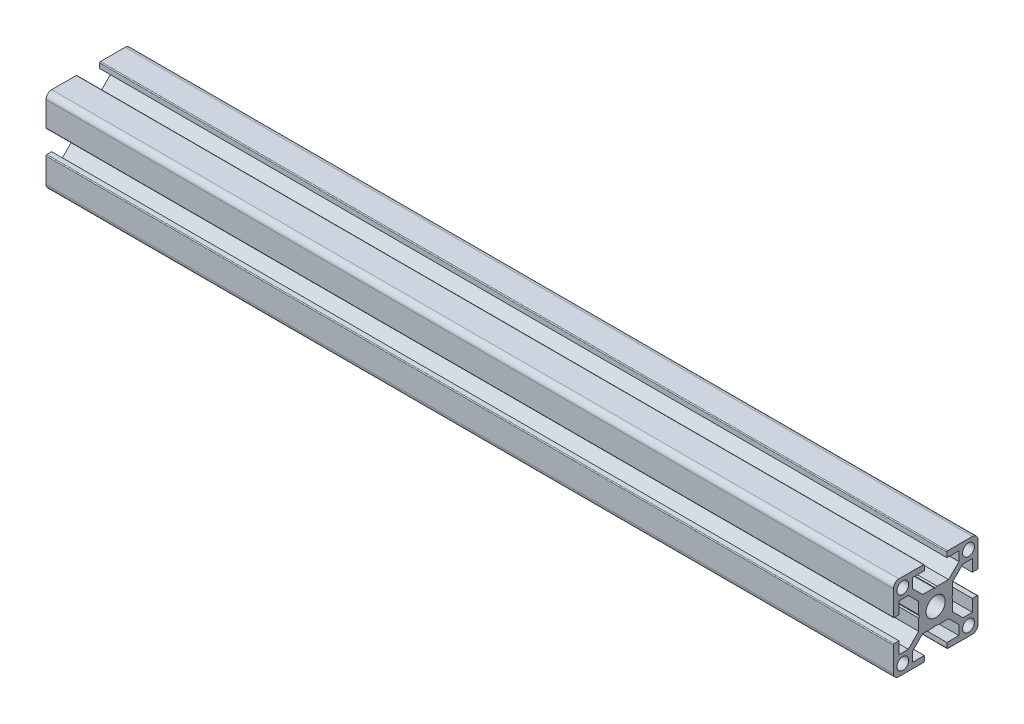
SolidWorks part; units mm, degrees
ref_plane "Front Plane" through (0, 0, 0) normal (0, 0, 1) x (1, 0, 0)
ref_plane "Top Plane" through (0, 0, 0) normal (0, 1, 0) x (1, 0, 0)
ref_plane "Right Plane" through (0, 0, 0) normal (1, 0, 0) x (0, 0, -1)
sketch "Sketch1" plane through (0, 0, 0) normal (0, 0, 1) x (1, 0, 0)
  line L0 (0, 0) -> (300, 0)
  dimension "D1" = 300
other "30xs6 30X30S6(1)"
ref_plane "Plane1" through (0, 0, 0) normal (1, 0, 0) x (0, 1, 0)
sketch "草图1" plane through (0, 0, 0) normal (1, 0, 0) x (0, 1, 0)
  line L0 (-14.7, 4) -> (-13, 4)
  line L1 (-13, 4) -> (-13, 8.25)
  line L2 (-13, 8.25) -> (-9.6642, 8.25)
  line L3 (-9.6642, 8.25) -> (-6, 4.5858)
  line L4 (-6, 4.5858) -> (-6, 0.5196)
  line L5 (-6, 0.5196) -> (-5.7, 0)
  line L6 (-5.7, 0) -> (-6, -0.5196)
  line L7 (-6, -0.5196) -> (-6, -4.5858)
  line L8 (-6, -4.5858) -> (-9.6642, -8.25)
  line L9 (-9.6642, -8.25) -> (-13, -8.25)
  line L10 (-13, -8.25) -> (-13, -4)
  line L11 (-13, -4) -> (-14.7, -4)
  line L12 (-15, -4.3) -> (-15, -13)
  line L13 (-13, -15) -> (-4.3, -15)
  line L14 (-4, -14.7) -> (-4, -13)
  line L15 (-4, -13) -> (-8.25, -13)
  line L16 (-8.25, -13) -> (-8.25, -9.6642)
  line L17 (-8.25, -9.6642) -> (-4.5858, -6)
  line L18 (-4.5858, -6) -> (-0.5196, -6)
  line L19 (-0.5196, -6) -> (0, -5.7)
  line L20 (0, -5.7) -> (0.5196, -6)
  line L21 (0.5196, -6) -> (4.5858, -6)
  line L22 (4.5858, -6) -> (8.25, -9.6642)
  line L23 (8.25, -9.6642) -> (8.25, -13)
  line L24 (8.25, -13) -> (4, -13)
  line L25 (4, -13) -> (4, -14.7)
  line L26 (4.3, -15) -> (13, -15)
  line L27 (15, -13) -> (15, -4.3)
  line L28 (14.7, -4) -> (13, -4)
  line L29 (13, -4) -> (13, -8.25)
  line L30 (13, -8.25) -> (9.6642, -8.25)
  line L31 (9.6642, -8.25) -> (6, -4.5858)
  line L32 (6, -4.5858) -> (6, -0.5196)
  line L33 (6, -0.5196) -> (5.7, 0)
  line L34 (5.7, 0) -> (6, 0.5196)
  line L35 (6, 0.5196) -> (6, 4.5858)
  line L36 (6, 4.5858) -> (9.6642, 8.25)
  line L37 (9.6642, 8.25) -> (13, 8.25)
  line L38 (13, 8.25) -> (13, 4)
  line L39 (13, 4) -> (14.7, 4)
  line L40 (15, 4.3) -> (15, 13)
  line L41 (13, 15) -> (4.3, 15)
  line L42 (4, 14.7) -> (4, 13)
  line L43 (4, 13) -> (8.25, 13)
  line L44 (8.25, 13) -> (8.25, 9.6642)
  line L45 (8.25, 9.6642) -> (4.5858, 6)
  line L46 (4.5858, 6) -> (0.5196, 6)
  line L47 (0.5196, 6) -> (0, 5.7)
  line L48 (0, 5.7) -> (-0.5196, 6)
  line L49 (-0.5196, 6) -> (-4.5858, 6)
  line L50 (-4.5858, 6) -> (-8.25, 9.6642)
  line L51 (-8.25, 9.6642) -> (-8.25, 13)
  line L52 (-8.25, 13) -> (-4, 13)
  line L53 (-4, 13) -> (-4, 14.7)
  line L54 (-4.3, 15) -> (-13, 15)
  line L55 (-15, 13) -> (-15, 4.3)
  arc A0 (-15, 4.3) -> (-14.7, 4) centre (-14.7, 4.3) ccw
  arc A1 (-14.7, -4) -> (-15, -4.3) centre (-14.7, -4.3) ccw
  arc A2 (-15, -13) -> (-13, -15) centre (-13, -13) ccw
  arc A3 (-4.3, -15) -> (-4, -14.7) centre (-4.3, -14.7) ccw
  arc A4 (4, -14.7) -> (4.3, -15) centre (4.3, -14.7) ccw
  arc A5 (13, -15) -> (15, -13) centre (13, -13) ccw
  arc A6 (15, -4.3) -> (14.7, -4) centre (14.7, -4.3) ccw
  arc A7 (14.7, 4) -> (15, 4.3) centre (14.7, 4.3) ccw
  arc A8 (15, 13) -> (13, 15) centre (13, 13) ccw
  arc A9 (4.3, 15) -> (4, 14.7) centre (4.3, 14.7) ccw
  arc A10 (-4, 14.7) -> (-4.3, 15) centre (-4.3, 14.7) ccw
  arc A11 (-13, 15) -> (-15, 13) centre (-13, 13) ccw
  circle A12 centre (11.625, 11.625) radius 2.1
  circle A13 centre (11.625, -11.625) radius 2.1
  circle A14 centre (0, 0) radius 3.4
  circle A15 centre (-11.625, -11.625) radius 2.1
  circle A16 centre (-11.625, 11.625) radius 2.1
  point P90 (-15, 15)
  point P91 (-0.2598, 14.9121)
  point P92 (15, 15)
  point P93 (15, 0)
  point P94 (15, -15)
  point P95 (0.2598, -15)
  point P96 (-15, -15)
  point P97 (-15, 0)
  point P98 (0, 0)
